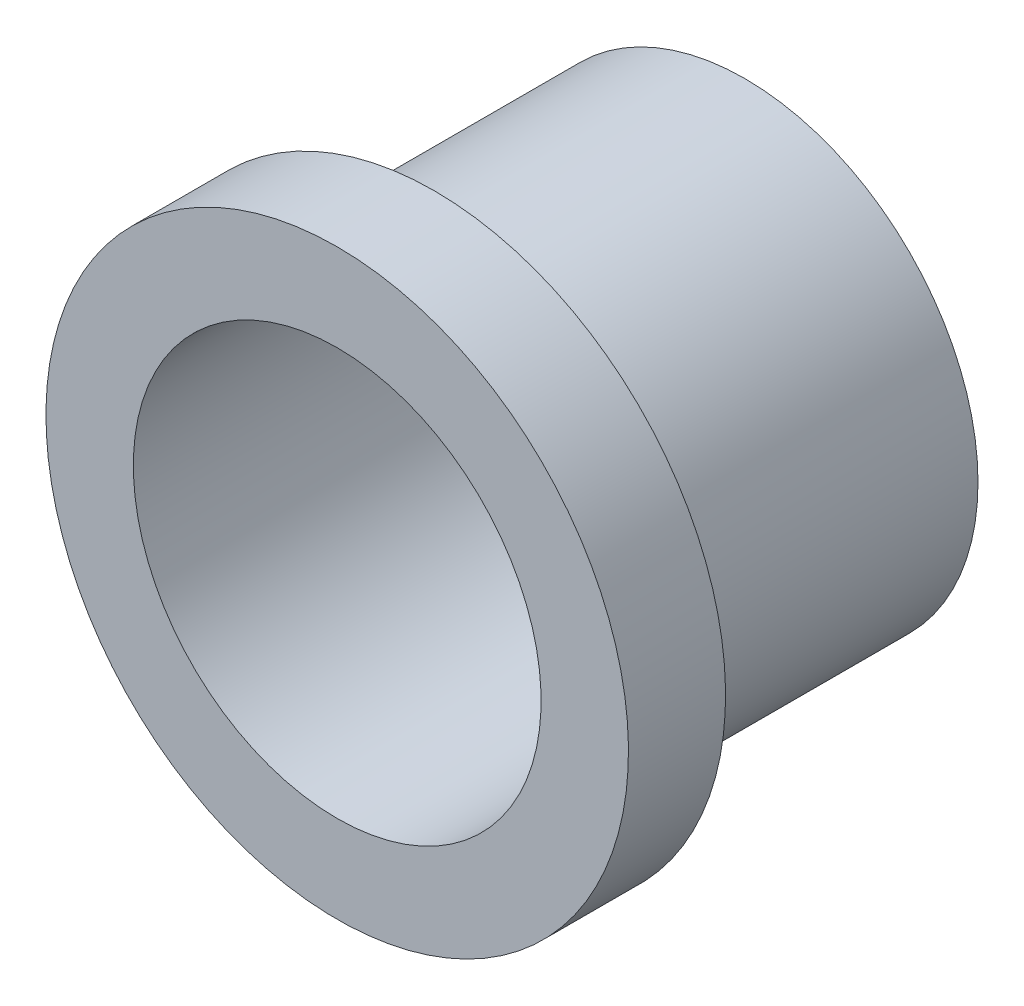
SolidWorks part; units mm, degrees
ref_plane "Front Plane" through (0, 0, 0) normal (0, 0, 1) x (1, 0, 0)
ref_plane "Top Plane" through (0, 0, 0) normal (0, 1, 0) x (1, 0, 0)
ref_plane "Right Plane" through (0, 0, 0) normal (1, 0, 0) x (0, 0, -1)
sketch "Sketch2" plane through (0, 0, 0) normal (1, 0, 0) x (0, 0, -1)
  line L0 (10.5, 0) -> (-10.5, 0)
  line L1 (-10.5, 0) -> (-10.5, 15)
  line L2 (-10.5, 15) -> (-5.5, 15)
  line L3 (-5.5, 15) -> (-5.5, 12)
  line L4 (10.5, 0) -> (10.5, 12)
  line L5 (10.5, 12) -> (-5.5, 12)
  line L6 (-10.5, 0) -> (0, 0)
  point P4 (0, 0)
  dimension "D1" = 21
  dimension "D2" = 16
  dimension "D3" = 12
  dimension "D4" = 15
revolve "Revolve1" add sketch "Sketch2" angle 360 about L0
sketch "Sketch3" plane through (0, 0, -10.5) normal (0, 0, -1) x (-1, 0, 0)
  circle A0 centre (0, 0) radius 10.5
  circle A1 centre (0, 0) radius 12 construction
  dimension "D1" = 21
extrude "Cut-Extrude1" cut sketch "Sketch3" against normal through all
